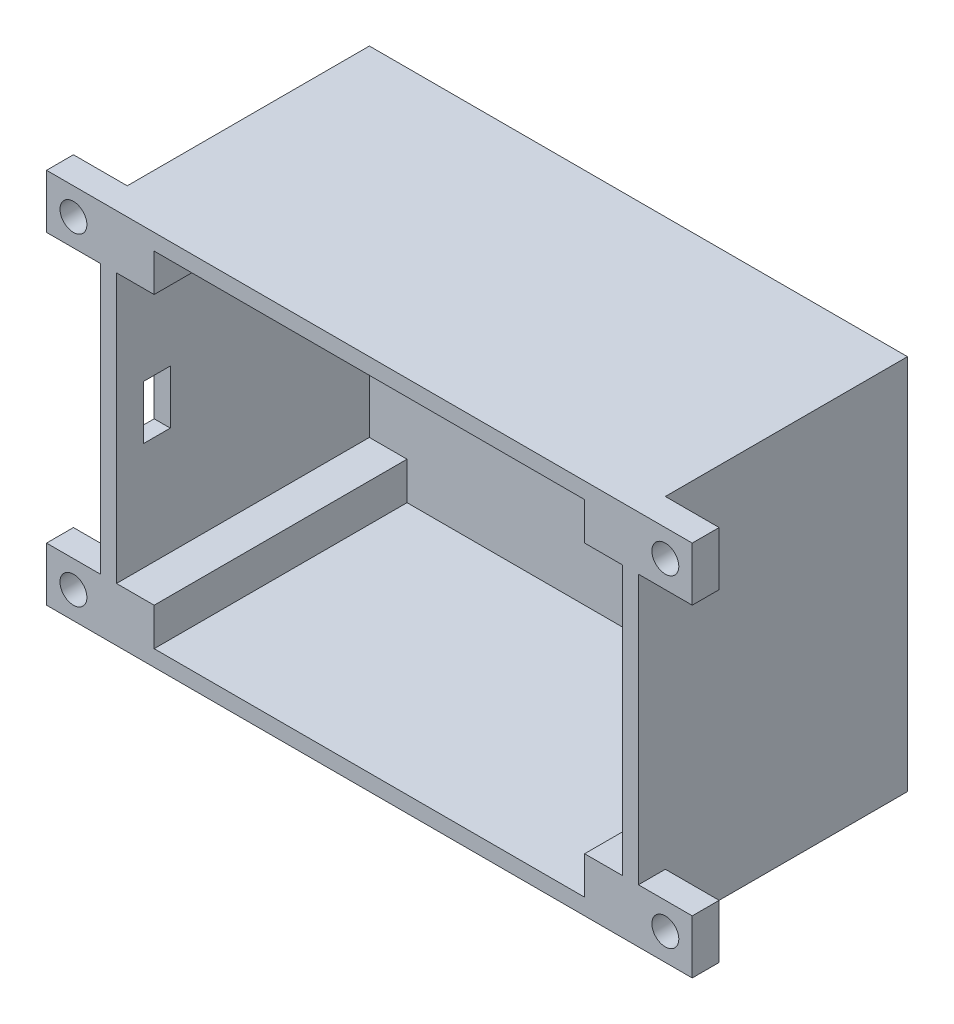
SolidWorks part; units mm, degrees
ref_plane "Plan de face" through (0, 0, 0) normal (0, 0, 1) x (1, 0, 0)
ref_plane "Plan de dessus" through (0, 0, 0) normal (0, 1, 0) x (1, 0, 0)
ref_plane "Plan de droite" through (0, 0, 0) normal (1, 0, 0) x (0, 0, -1)
sketch "Esquisse1" plane through (0, 0, 0) normal (0, 0, 1) x (1, 0, 0)
  line L1 (0, 0) -> (-100, 0)
  line L2 (0, 0) -> (0, 70)
  line L3 (0, 70) -> (-100, 70)
  line L4 (-100, 0) -> (-100, 70)
  dimension "D1" = 100
  dimension "D2" = 70
extrude "Boss.-Extru.1" add sketch "Esquisse1" along normal blind 50
sketch "Esquisse2" plane through (0, 0, 50) normal (0, 0, 1) x (1, 0, 0)
  line L0 (0, 70) -> (-100, 70) construction
  line L1 (-97, 67) -> (-3, 67)
  line L2 (-97, 67) -> (-97, 3)
  line L3 (-97, 3) -> (-3, 3)
  line L4 (-3, 67) -> (-3, 3)
  line L5 (-100, 0) -> (0, 0) construction
  line L6 (-100, 70) -> (-100, 0) construction
  line L7 (0, 0) -> (0, 70) construction
  dimension "D1" = 3
  dimension "D2" = 3
  dimension "D3" = 3
  dimension "D4" = 3
extrude "Enlèv. mat.-Extru.1" cut sketch "Esquisse2" against normal blind 47
sketch "Esquisse3" plane through (-100, 0, 0) normal (-1, 0, 0) x (0, 0, 1)
  line L1 (40, 40) -> (45, 40)
  line L2 (40, 40) -> (40, 30)
  line L3 (40, 30) -> (45, 30)
  line L4 (45, 40) -> (45, 30)
  line L6 (50, 70) -> (0, 70) construction
  line L7 (0, 70) -> (0, 0) construction
  dimension "D1" = 10
  dimension "D2" = 5
  dimension "D3" = 30
  dimension "D4" = 40
sketch "Esquisse4" plane through (0, 0, 0) normal (0, 0, -1) x (-1, 0, 0)
  line L1 (42.5, 30) -> (57.5, 30)
  line L2 (42.5, 30) -> (42.5, 40)
  line L3 (42.5, 40) -> (57.5, 40)
  line L4 (57.5, 30) -> (57.5, 40)
  line L12 (0, 70) -> (100, 70) construction
  dimension "D1" = 15
  dimension "D2" = 10
  dimension "D3" = 30
extrude "Enlèv. mat.-Extru.3" cut sketch "Esquisse4" against normal blind 47
sketch "Esquisse5" plane through (0, 0, 0) normal (0, 0, -1) x (-1, 0, 0)
  line L0 (100, 0) -> (0, 0) construction
  line L1 (10, 0) -> (-10, 0)
  line L2 (10, 0) -> (10, 10)
  line L3 (10, 10) -> (-10, 10)
  line L4 (-10, 0) -> (-10, 10)
  line L5 (0, 0) -> (0, 70) construction
  line L6 (0, 70) -> (100, 70) construction
  line L7 (10, 70) -> (-10, 70)
  line L8 (10, 70) -> (10, 60)
  line L9 (10, 60) -> (-10, 60)
  line L10 (-10, 70) -> (-10, 60)
  line L11 (100, 70) -> (100, 0) construction
  line L12 (90, 0) -> (110, 0)
  line L13 (90, 0) -> (90, 10)
  line L14 (90, 10) -> (110, 10)
  line L15 (110, 0) -> (110, 10)
  line L16 (90, 60) -> (110, 60)
  line L17 (90, 60) -> (90, 70)
  line L18 (90, 70) -> (110, 70)
  line L19 (110, 60) -> (110, 70)
  dimension "D1" = 10
  dimension "D2" = 20
  dimension "D3" = 10
  dimension "D4" = 10
  dimension "D5" = 10
  dimension "D6" = 10
  dimension "D7" = 20
  dimension "D8" = 10
  dimension "D9" = 20
  dimension "D10" = 10
extrude "Boss.-Extru.2" add sketch "Esquisse5" against normal blind 50
sketch "Esquisse6" plane through (0, 0, 0) normal (0, 0, -1) x (-1, 0, 0)
  line L0 (110, 0) -> (-10, 0) construction
  line L1 (-10, 70) -> (0, 70)
  line L2 (-10, 70) -> (-10, 60)
  line L3 (-10, 60) -> (0, 60)
  line L4 (0, 70) -> (0, 60)
  line L5 (-10, 10) -> (0, 10)
  line L6 (-10, 10) -> (-10, 0)
  line L7 (-10, 0) -> (0, 0)
  line L8 (0, 10) -> (0, 0)
  line L9 (110, 70) -> (100, 70)
  line L10 (110, 70) -> (110, 60)
  line L11 (110, 60) -> (100, 60)
  line L12 (100, 70) -> (100, 60)
  line L13 (110, 10) -> (100, 10)
  line L14 (110, 10) -> (110, 0)
  line L15 (110, 0) -> (100, 0)
  line L16 (100, 10) -> (100, 0)
extrude "Enlèv. mat.-Extru.4" cut sketch "Esquisse6" against normal blind 45
sketch "Esquisse7" plane through (0, 0, 45) normal (0, 0, -1) x (-1, 0, 0)
  line L0 (-10, 65) -> (0, 65) construction
  line L1 (-10, 70) -> (-10, 60) construction
  line L2 (0, 60) -> (0, 70) construction
  line L3 (-5, 70) -> (-5, 60) construction
  line L4 (0, 70) -> (-10, 70) construction
  line L5 (-10, 60) -> (0, 60) construction
  line L6 (-5, 10) -> (-5, 0) construction
  line L7 (0, 10) -> (-10, 10) construction
  line L8 (-10, 0) -> (0, 0) construction
  line L9 (-10, 5) -> (0, 5) construction
  line L10 (-10, 10) -> (-10, 0) construction
  line L11 (0, 0) -> (0, 10) construction
  line L12 (110, 65) -> (100, 65) construction
  line L13 (110, 60) -> (110, 70) construction
  line L14 (100, 70) -> (100, 60) construction
  line L15 (105, 70) -> (105, 60) construction
  line L16 (110, 70) -> (100, 70) construction
  line L17 (100, 60) -> (110, 60) construction
  line L18 (100, 5) -> (110, 5) construction
  line L19 (100, 10) -> (100, 0) construction
  line L20 (110, 0) -> (110, 10) construction
  line L21 (105, 10) -> (105, 0) construction
  line L22 (110, 10) -> (100, 10) construction
  line L23 (100, 0) -> (110, 0) construction
  circle A0 centre (-5, 65) radius 2.5
  circle A1 centre (-5, 5) radius 2.5
  circle A2 centre (105, 5) radius 2.5
  circle A3 centre (105, 65) radius 2.5
  dimension "D1" = 5
  dimension "D2" = 5
  dimension "D3" = 5
  dimension "D4" = 5
extrude "Enlèv. mat.-Extru.5" cut sketch "Esquisse7" against normal blind 45
extrude "Enlèv. mat.-Extru.6" cut sketch "Esquisse3" against normal blind 45
